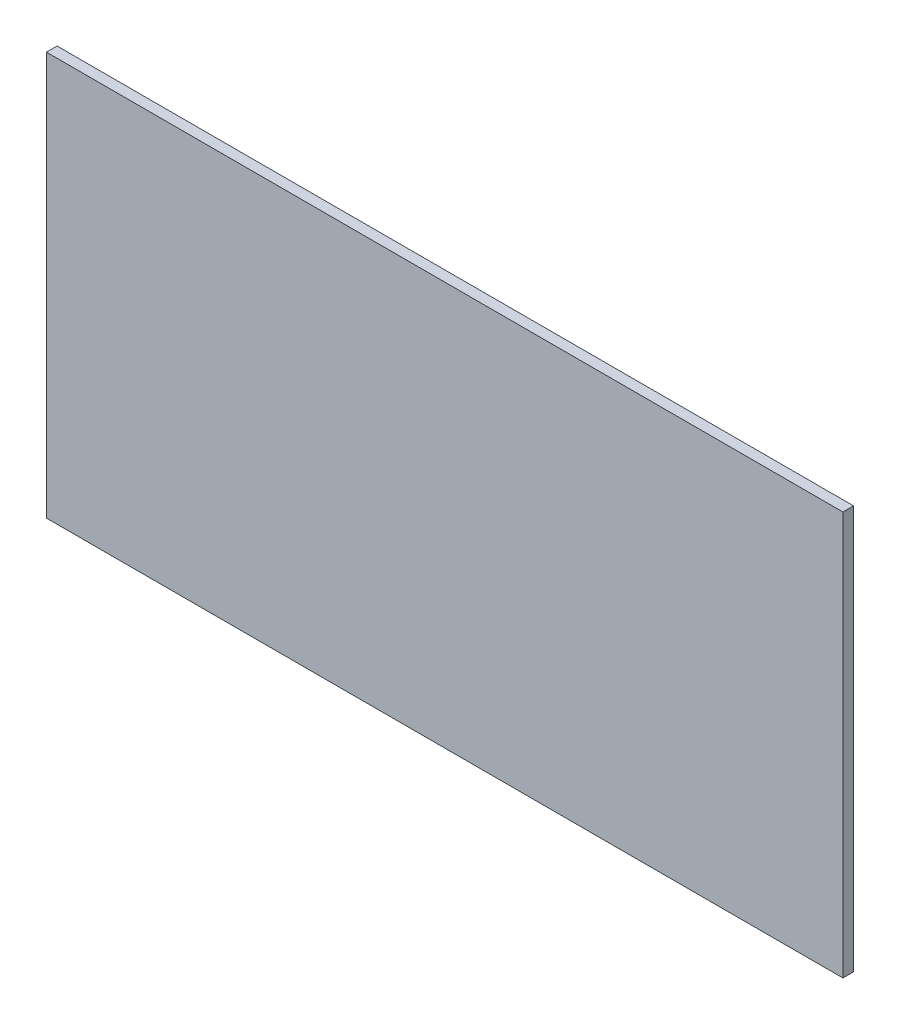
SolidWorks part; units mm, degrees
ref_plane "Front Plane" through (0, 0, 0) normal (0, 0, 1) x (1, 0, 0)
ref_plane "Top Plane" through (0, 0, 0) normal (0, 1, 0) x (1, 0, 0)
ref_plane "Right Plane" through (0, 0, 0) normal (1, 0, 0) x (0, 0, -1)
sketch "Sketch1" plane through (0, 0, 0) normal (0, 0, 1) x (1, 0, 0)
  line L1 (-37.5, -19) -> (37.5, -19)
  line L2 (-37.5, -19) -> (-37.5, 19)
  line L3 (-37.5, 19) -> (37.5, 19)
  line L4 (37.5, -19) -> (37.5, 19)
  line L5 (-37.5, -19) -> (37.5, 19) construction
  line L6 (-37.5, 19) -> (37.5, -19) construction
  point P0 (0, 0)
  dimension "D1" = 38
  dimension "D2" = 75
extrude "Boss-Extrude1" add sketch "Sketch1" along normal blind 1
